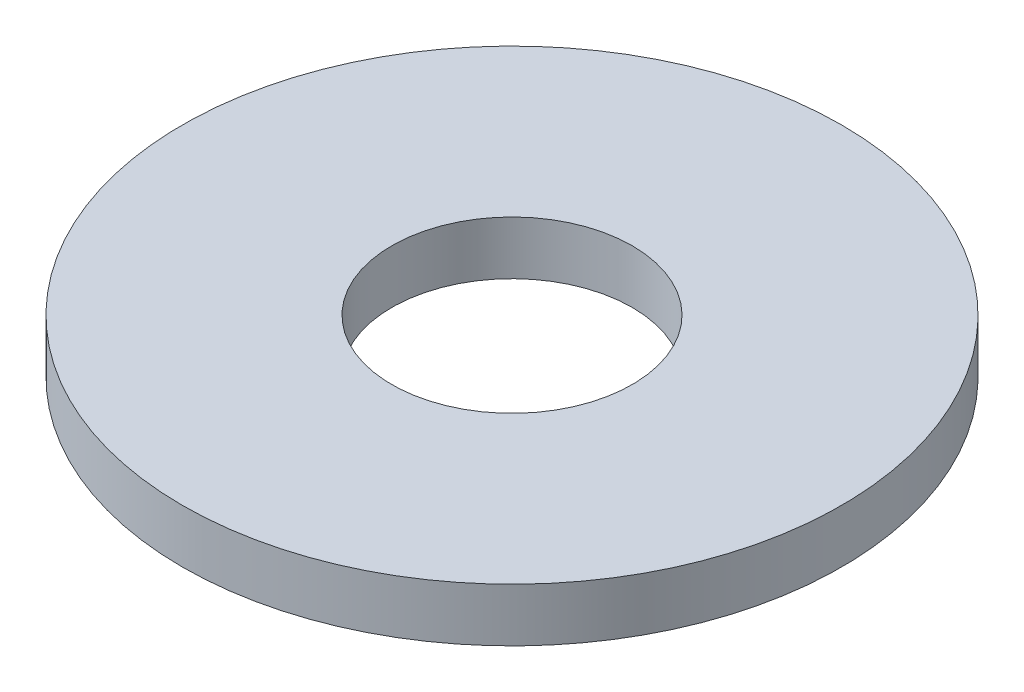
SolidWorks part; units mm, degrees
ref_plane "基准面1" through (0, 0, 0) normal (0, 0, 1) x (1, 0, 0)
ref_plane "基准面2" through (0, 0, 0) normal (0, 1, 0) x (1, 0, 0)
ref_plane "基准面3" through (0, 0, 0) normal (1, 0, 0) x (0, 0, -1)
sketch "尺寸草图" plane through (0, 0, 0) normal (0, 0, 1) x (1, 0, 0)
  line L0 (0, 0) -> (37, 0) construction
  point P3 (3, 0)
  point P4 (37, 0)
  point P5 (13.5, 0)
  dimension "h" = 3
  dimension "d2" = 37
  dimension "d1" = 13.5
sketch "草图1" plane through (0, 0, 0) normal (0, 0, 1) x (1, 0, 0)
  line L0 (0, 0) -> (0, 52.7318) construction
  line L2 (-6.75, 8.6445) -> (-18.5, 8.6445)
  line L3 (-6.75, 8.6445) -> (-6.75, 11.6445)
  line L4 (-6.75, 11.6445) -> (-18.5, 11.6445)
  line L5 (-18.5, 8.6445) -> (-18.5, 11.6445)
  dimension "D1" = 6.75
  dimension "D2" = 18.5
  dimension "h" = 3
revolve "基体-旋转" add sketch "草图1" angle 360 about L0
